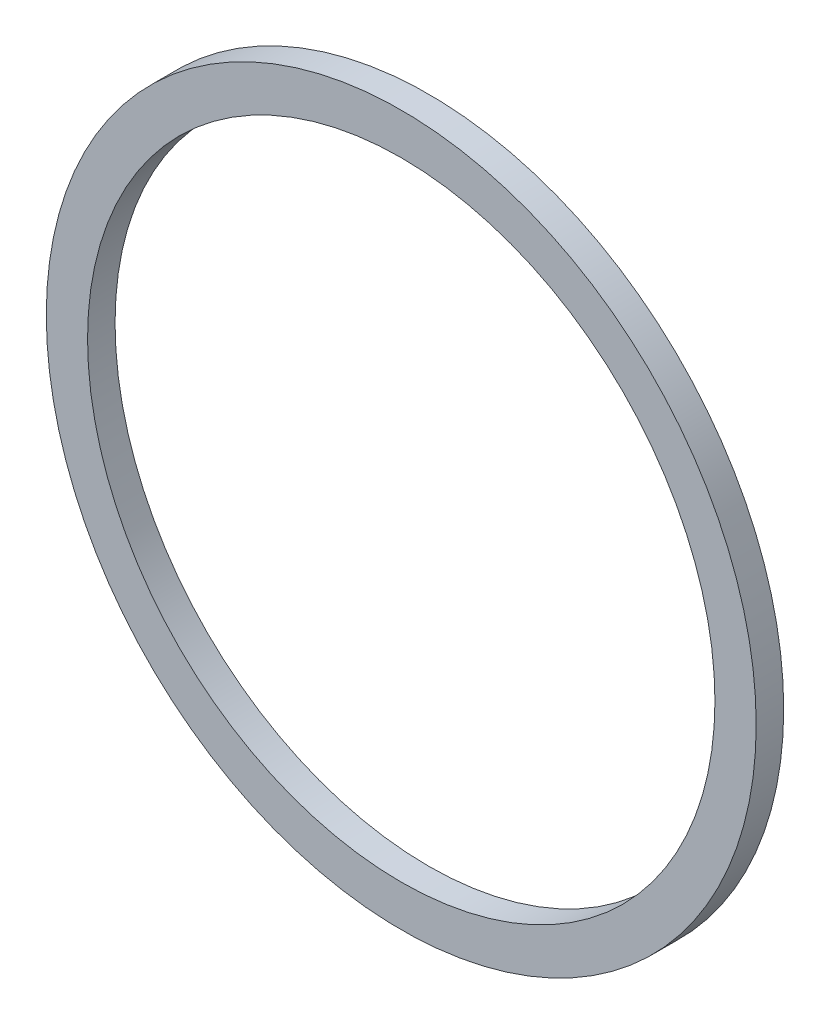
SolidWorks part; units mm, degrees
ref_plane "Front Plane" through (0, 0, 0) normal (0, 0, 1) x (1, 0, 0)
ref_plane "Top Plane" through (0, 0, 0) normal (0, 1, 0) x (1, 0, 0)
ref_plane "Right Plane" through (0, 0, 0) normal (1, 0, 0) x (0, 0, -1)
sketch "Sketch1" plane through (0, 0, 0) normal (0, 0, 1) x (1, 0, 0)
  circle A0 centre (0, -76.2) radius 81.9404 construction
  circle A1 centre (0, -76.2) radius 81.9404
  circle A2 centre (0, -76.2) radius 72.4154
  dimension "D1" = 9.525
extrude "Boss-Extrude1" add sketch "Sketch1" along normal blind 6.35
